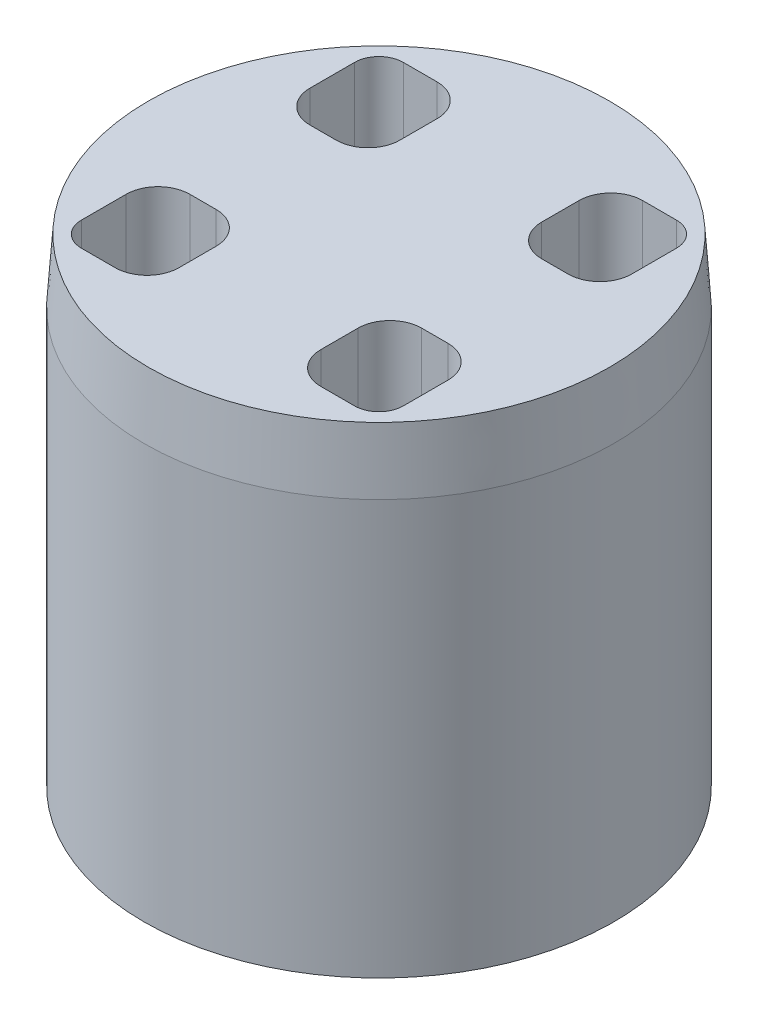
SolidWorks part; units mm, degrees
ref_plane "Front Plane" through (0, 0, 0) normal (0, 0, 1) x (1, 0, 0)
ref_plane "Top Plane" through (0, 0, 0) normal (0, 1, 0) x (1, 0, 0)
ref_plane "Right Plane" through (0, 0, 0) normal (1, 0, 0) x (0, 0, -1)
sketch "Sketch2" plane through (0, 0, 0) normal (0, 1, 0) x (1, 0, 0)
  line L1 (42.87, -50.5) -> (-42.87, -50.5)
  line L2 (50.5, -42.87) -> (50.5, 42.87)
  line L3 (42.87, 50.5) -> (-42.87, 50.5)
  line L4 (-50.5, -42.87) -> (-50.5, 42.87)
  line L5 (50.5, -50.5) -> (-50.5, 50.5) construction
  line L6 (50.5, 50.5) -> (-50.5, -50.5) construction
  circle A0 centre (0, 0) radius 73.75
  arc A1 (-42.87, 50.5) -> (-50.5, 42.87) centre (-42.87, 42.87) ccw
  arc A2 (-42.87, -50.5) -> (-50.5, -42.87) centre (-42.87, -42.87) cw
  arc A3 (42.87, -50.5) -> (50.5, -42.87) centre (42.87, -42.87) ccw
  arc A4 (50.5, 42.87) -> (42.87, 50.5) centre (42.87, 42.87) ccw
  dimension "D1" = 147.5
  dimension "D4" = 7.63
  dimension "D2" = 101
  dimension "D3" = 101
extrude "MainDoughnut" add sketch "Sketch2" along normal blind 150
sketch "Sketch3" plane through (0, 150, 0) normal (0, 1, 0) x (1, 0, 0)
  circle A0 centre (0, 0) radius 62.7115 construction
  circle A1 centre (-62.7115, 0) radius 3.81
  circle A2 centre (0, 62.7115) radius 3.81
  circle A3 centre (62.7115, 0) radius 3.81
  circle A4 centre (0, -62.7115) radius 3.81
  point P14 (0, 0)
  dimension "D1" = 7.62
  dimension "D2" = 4
extrude "Cut-Extrude1" cut sketch "Sketch3" against normal through all
chamfer "NoseconeTaper" distance 20 angle 4 1 edges at (0, 150, 73.75)
sketch "Sketch5" plane through (0, 150, 0) normal (0, 1, 0) x (1, 0, 0)
  line L0 (-42.87, -50.5) -> (42.87, -50.5) construction
  line L5 (-22.2517, 28.8295) -> (-22.2517, 68.8447)
  line L6 (22.2517, -67.5462) -> (-22.2517, -67.5462)
  line L7 (-55, 0) -> (55, 0) construction
  line L12 (22.2517, -67.5462) -> (22.2517, -28.8295)
  line L13 (22.2517, 68.8447) -> (-22.2517, 68.8447)
  line L14 (-50.5, 42.87) -> (-50.5, -42.87) construction
  line L19 (-22.2517, -67.5462) -> (-22.2517, -28.8295)
  line L21 (0, -55) -> (0, 55) construction
  line L27 (68.5789, 18.8295) -> (32.2517, 18.8295)
  line L28 (68.5789, 18.8295) -> (68.5789, -18.8295)
  line L29 (68.5789, -18.8295) -> (32.2517, -18.8295)
  line L30 (-69.8583, 18.8295) -> (-69.8583, -18.8295)
  line L37 (22.2517, 28.8295) -> (22.2517, 68.8447)
  line L38 (-32.2517, 18.8295) -> (-69.8583, 18.8295)
  line L39 (-32.2517, -18.8295) -> (-69.8583, -18.8295)
  circle A9 centre (0, 0) radius 72.3515 construction
  arc A10 (-22.2517, -28.8295) -> (-32.2517, -18.8295) centre (-32.2517, -28.8295) ccw
  arc A11 (22.2517, -28.8295) -> (32.2517, -18.8295) centre (32.2517, -28.8295) cw
  arc A12 (22.2517, 28.8295) -> (32.2517, 18.8295) centre (32.2517, 28.8295) ccw
  arc A13 (-22.2517, 28.8295) -> (-32.2517, 18.8295) centre (-32.2517, 28.8295) cw
  point P0 (0, -50.5)
  point P1 (0, 0)
  point P12 (0, 0)
  point P15 (0, 50.5)
  point P16 (-50.5, 0)
  point P26 (-22.2517, -18.8295)
  point P29 (50.5, 0)
  point P37 (-22.2517, 18.8295)
  dimension "D1" = 10
extrude "PayloadStops" add sketch "Sketch5" against normal blind 90
fillet "Fillet1" radius 10 1 edges at (-22.2517, 105, -50.5)
fillet "Fillet2" radius 10 1 edges at (-50.5, 105, -18.8295)
fillet "Fillet3" radius 10 6 edges at (-50.5, 105, 18.8295) (22.2517, 105, -50.5) (50.5, 105, -18.8295) (50.5, 105, 18.8295) (22.2517, 105, 50.5) (-22.2517, 105, 50.5)
chamfer "Chamfer1" distance 3 angle 45 8 edges at (-50.5, 0, 0) (-48.2652, 0, -48.2652) (-48.2652, 0, 48.2652) (0, 0, -50.5) (48.2652, 0, -48.2652) (50.5, 0, 0) (48.2652, 0, 48.2652) (0, 0, 50.5)
